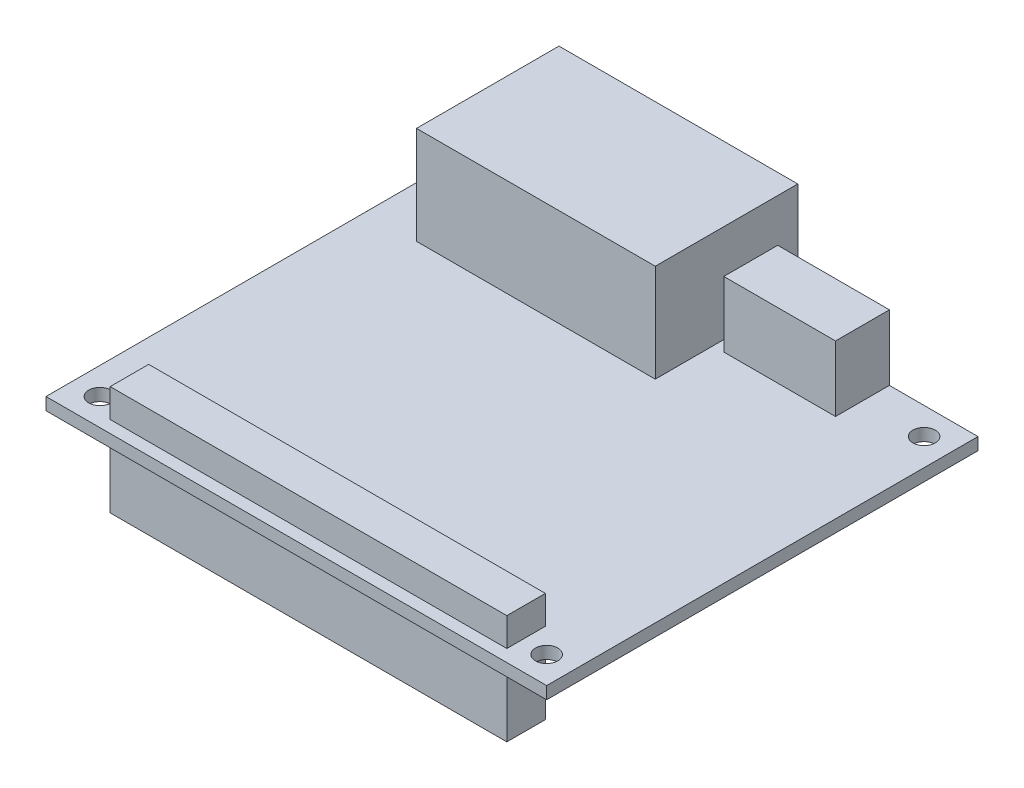
SolidWorks part; units mm, degrees
ref_plane "Plan de face" through (0, 0, 0) normal (0, 0, 1) x (1, 0, 0)
ref_plane "Plan de dessus" through (0, 0, 0) normal (0, 1, 0) x (1, 0, 0)
ref_plane "Plan de droite" through (0, 0, 0) normal (1, 0, 0) x (0, 0, -1)
sketch "Esquisse1" plane through (0, 0, 0) normal (0, 1, 0) x (1, 0, 0)
  line L0 (-32.5, -28) -> (32.5, 28) construction
  line L1 (-32.5, 28) -> (32.5, 28)
  line L2 (-32.5, 28) -> (-32.5, -28)
  line L3 (-32.5, -28) -> (32.5, -28)
  line L4 (32.5, 28) -> (32.5, -28)
  point P4 (0, 0)
  dimension "D1" = 65
  dimension "D2" = 56
extrude "Boss.-Extru.1" add sketch "Esquisse1" along normal blind 1.6
hole_wizard "Dégagement M2.51" positions "Esquisse2" profile "Esquisse3" hole size "M2.5" standard "ISO" end condition through all
sketch "Esquisse2" plane through (0, 1.6, 0) normal (0, 1, 0) x (1, 0, 0)
  line L0 (0, 0) -> (0, 7.4913) construction
  line L2 (0, 0) -> (5.886, 0) construction
  point P0 (-29, 24.5)
  point P11 (29, 24.5)
  point P12 (29, -24.5)
  point P13 (-29, -24.5)
  dimension "D1" = 58
  dimension "D2" = 49
sketch "Esquisse3" plane through (-29, 1.6, -24.5) normal (1, 0, 0) x (0, 0, 1)
  line L0 (0, 0) -> (0, 1.6)
  line L1 (0, 1.6) -> (1.45, 1.6)
  line L2 (1.45, 1.6) -> (1.45, 0)
  line L5 (1.45, 0) -> (0, 0)
  line L11 (0, -6.35) -> (0, 107.95) construction
  dimension "Diamètre du perçage jusqu'au prochain" = 2.9
  dimension "Profondeur du perçage jusqu'au prochain" = 1.6
sketch "Esquisse4" plane through (0, 1.6, 0) normal (0, 1, 0) x (1, 0, 0)
  line L0 (-32.5, 28) -> (-32.5, -28) construction
  line L1 (-25.9, 32) -> (5.1, 32)
  line L2 (-25.9, 32) -> (-25.9, 13.5)
  line L3 (-25.9, 13.5) -> (5.1, 13.5)
  line L4 (5.1, 32) -> (5.1, 13.5)
  line L5 (32.5, 28) -> (-32.5, 28) construction
  dimension "D1" = 18.5
  dimension "D2" = 31
  dimension "D3" = 6.6
  dimension "D4" = 4
extrude "Boss.-Extru.2" add sketch "Esquisse4" along normal blind 12.7 separate body
sketch "Esquisse5" plane through (0, 1.6, 0) normal (0, 1, 0) x (1, 0, 0)
  line L0 (32.5, -28) -> (32.5, 28) construction
  line L1 (6.5, 28) -> (21, 28)
  line L2 (6.5, 28) -> (6.5, 21)
  line L3 (6.5, 21) -> (21, 21)
  line L4 (21, 28) -> (21, 21)
  line L5 (32.5, 28) -> (-32.5, 28) construction
  dimension "D1" = 14.5
  dimension "D2" = 7
  dimension "D3" = 11.5
extrude "Boss.-Extru.3" add sketch "Esquisse5" along normal blind 8.5 separate body
sketch "Esquisse6" plane through (0, 1.6, 0) normal (0, 1, 0) x (1, 0, 0)
  line L1 (-25.75, -21.4201) -> (25.75, -21.4201)
  line L2 (-25.75, -21.4201) -> (-25.75, -26.4201)
  line L3 (-25.75, -26.4201) -> (25.75, -26.4201)
  line L4 (25.75, -21.4201) -> (25.75, -26.4201)
  point P4 (0, -21.4201)
  dimension "D1" = 5
  dimension "D2" = 51.5
extrude "Boss.-Extru.4" add sketch "Esquisse6" along normal blind 3.7 and the other way blind 10.5 separate body
